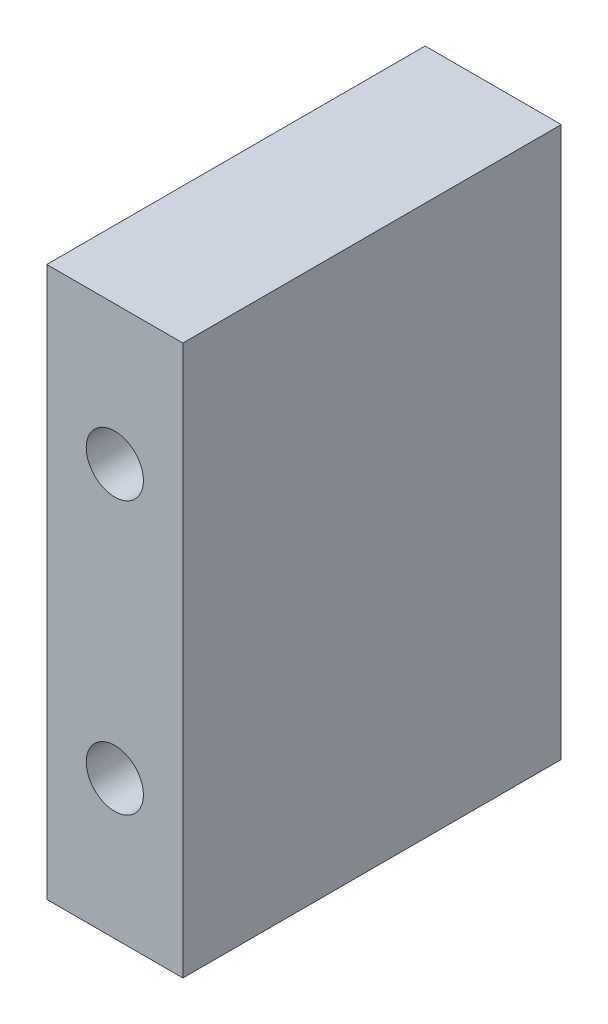
SolidWorks part; units mm, degrees
material "ABS"
ref_plane "Front" through (0, 0, 0) normal (0, 0, 1) x (1, 0, 0)
ref_plane "Top" through (0, 0, 0) normal (0, 1, 0) x (1, 0, 0)
ref_plane "Right" through (0, 0, 0) normal (1, 0, 0) x (0, 0, -1)
sketch "Esquisse1" plane through (0, 0, 0) normal (0, 0, 1) x (1, 0, 0)
  line L1 (-2.5, 10.1) -> (2.5, 10.1)
  line L2 (-2.5, 10.1) -> (-2.5, -10.1)
  line L3 (-2.5, -10.1) -> (2.5, -10.1)
  line L4 (2.5, 10.1) -> (2.5, -10.1)
  line L5 (-2.5, 10.1) -> (2.5, -10.1) construction
  line L6 (-2.5, -10.1) -> (2.5, 10.1) construction
  point P0 (0, 0)
  dimension "D1" = 5
  dimension "D2" = 20.2
extrude "Boss.-Extru.1" add sketch "Esquisse1" along normal blind 13.9
sketch "Esquisse4" plane through (0, 0, 0) normal (0, 0, -1) x (-1, 0, 0)
  line L0 (-2.5, 10.1) -> (2.5, 10.1) construction
  line L1 (-2.5, -10.1) -> (-2.5, 10.1) construction
  circle A0 centre (0, 5) radius 1.05
  circle A2 centre (0, -5) radius 1.05
  dimension "D1" = 2
  dimension "D2" = 5.1
  dimension "D3" = 2.1
  dimension "D4" = 2.5
extrude "Enlèv. mat.-Extru.1" cut sketch "Esquisse4" against normal through all
